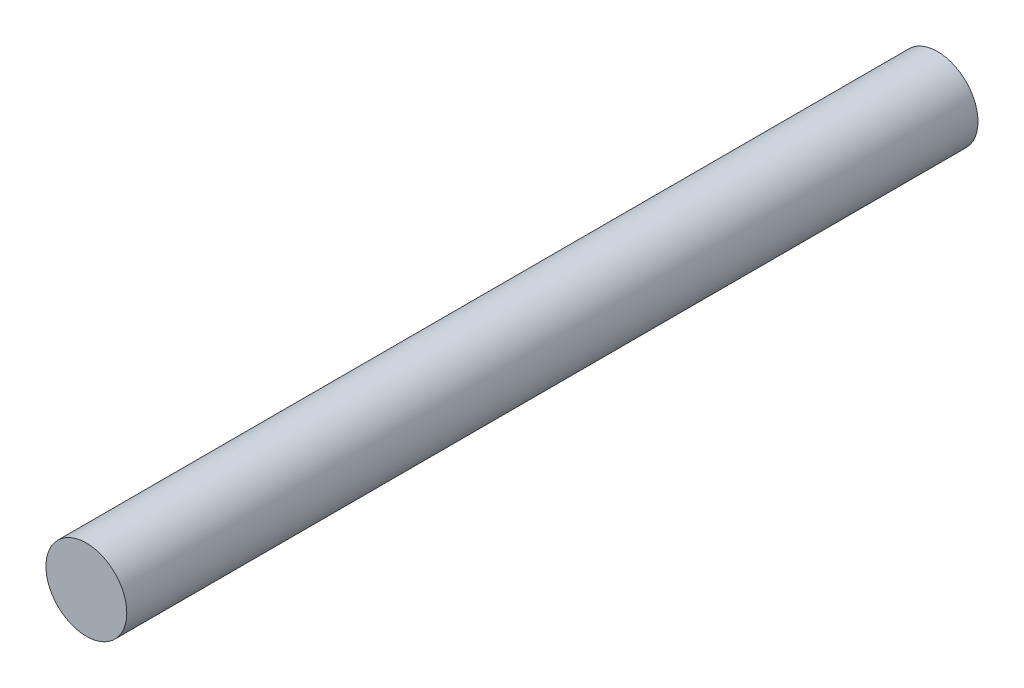
SolidWorks part; units mm, degrees
ref_plane "Front Plane" through (0, 0, 0) normal (0, 0, 1) x (1, 0, 0)
ref_plane "Top Plane" through (0, 0, 0) normal (0, 1, 0) x (1, 0, 0)
ref_plane "Right Plane" through (0, 0, 0) normal (1, 0, 0) x (0, 0, -1)
sketch "Sketch1" plane through (0, 0, 0) normal (0, 0, 1) x (1, 0, 0)
  circle A0 centre (0, 0) radius 4.826
extrude "Boss-Extrude1" add sketch "Sketch1" along normal blind 101.6
